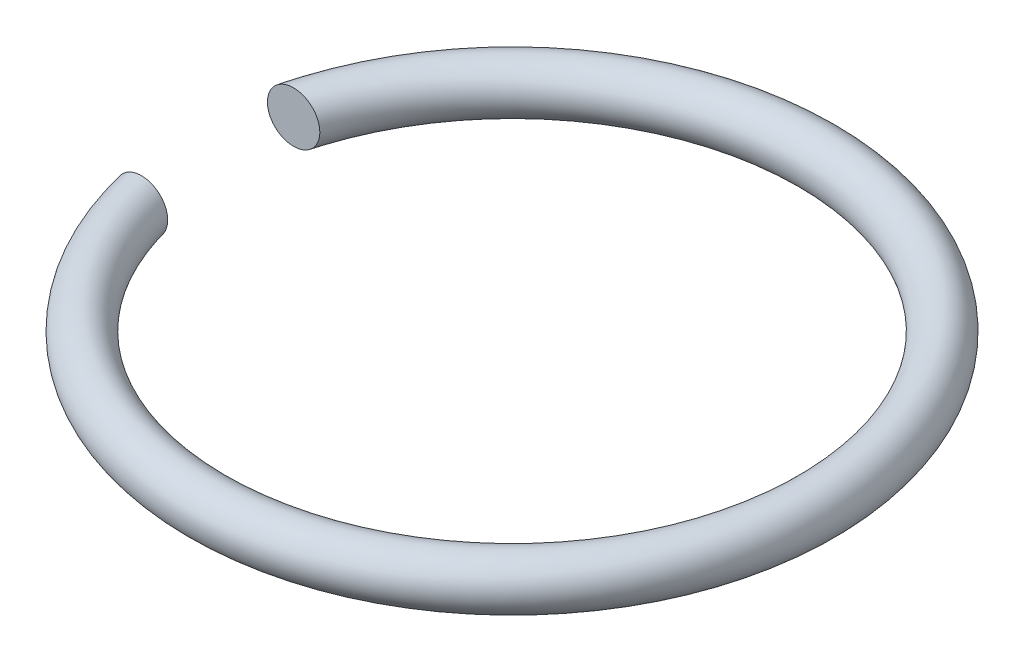
SolidWorks part; units mm, degrees
material "AISI 304"
ref_plane "Спереди" through (0, 0, 0) normal (0, 0, 1) x (1, 0, 0)
ref_plane "Сверху" through (0, 0, 0) normal (0, 1, 0) x (1, 0, 0)
ref_plane "Справа" through (0, 0, 0) normal (1, 0, 0) x (0, 0, -1)
sketch "Эскиз1" plane through (0, 0, 0) normal (0, 0, 1) x (1, 0, 0)
  line L0 (0, 0) -> (0, 5.376) construction
  circle A0 centre (-12, 1) radius 1
  dimension "D1" = 2
  dimension "D2" = 12
  dimension "D3" = 1
revolve "Повернуть1" add sketch "Эскиз1" angle 360 about L0
sketch "Эскиз2" plane through (0, 0, 0) normal (0, 1, 0) x (1, 0, 0)
  line L0 (0, 0) -> (-16.7656, 0) construction
  line L1 (-18.61, 3) -> (-0.3581, 3)
  line L2 (-18.61, 3) -> (-18.61, -3)
  line L3 (-18.61, -3) -> (-0.3581, -3)
  line L4 (-0.3581, 3) -> (-0.3581, -3)
  dimension "D1" = 3
  dimension "D2" = 3
extrude "Вырез-Вытянуть1" cut sketch "Эскиз2" against normal through all and the other way through all
ref_plane "Плоскость1" through (0, 0, 0) normal (0, -1, 0) x (-1, 0, 0)
